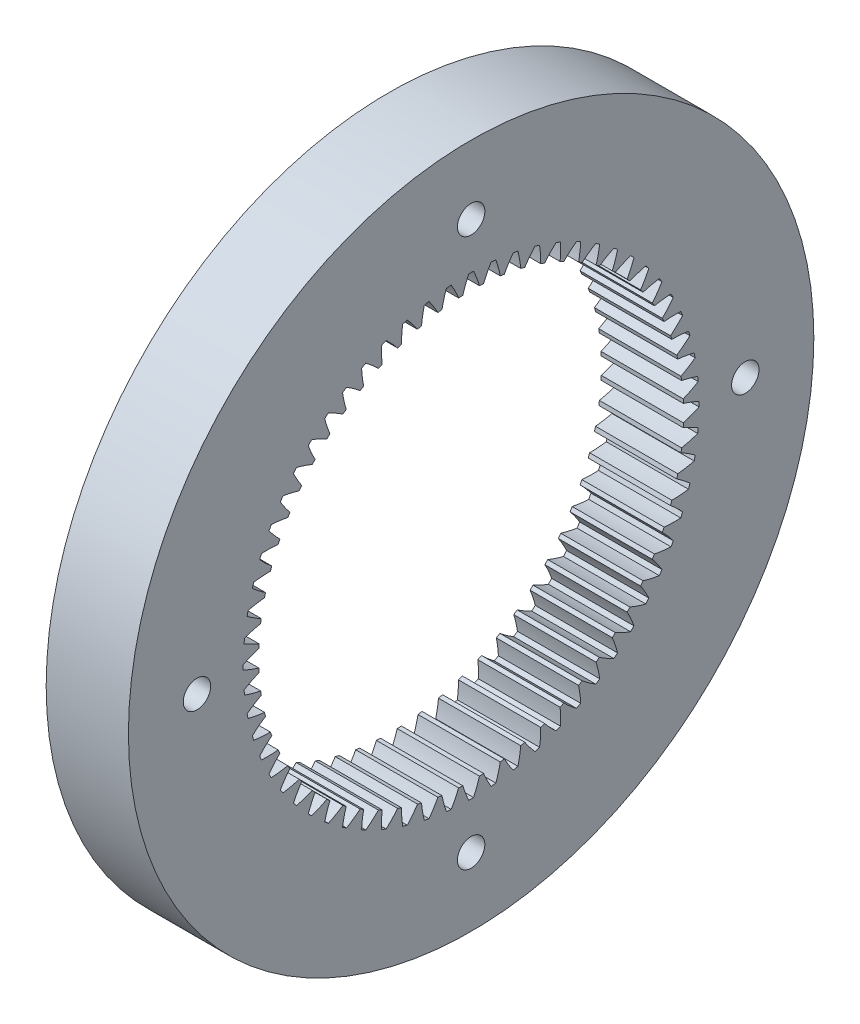
SolidWorks part; units mm, degrees
ref_plane "Plane1" through (0, 0, 0) normal (0, 0, 1) x (1, 0, 0)
ref_plane "Plane2" through (0, 0, 0) normal (0, 1, 0) x (1, 0, 0)
ref_plane "Plane3" through (0, 0, 0) normal (1, 0, 0) x (0, 0, -1)
sketch "HoldingSke" plane through (0, 0, 0) normal (0, 1, 0) x (1, 0, 0)
  line L0 (0, 0) -> (0.4384, -0.8988)
  line L1 (-15, 0) -> (100, 0) construction
  line L2 (0, 0) -> (-2.1039, 2.3779)
  line L3 (0, 0) -> (-11.863, 4.5341)
  line L4 (0, 0) -> (3.7858, 7.762)
  line L5 (0, 0) -> (-23.7986, -8.8762)
  line L6 (0, 0) -> (-10.5278, -7.1032)
  line L7 (-2.1039, 2.3779) -> (3.3635, 27.1825)
  line L8 (-76.2, 3.3779) -> (-54.61, 3.3779)
  line L9 (-71.009, 38.7566) -> (-53.1078, 45.2721)
  line L10 (-76.2, 71.12) -> (104.1128, 71.12)
  line L11 (0, 0) -> (-12, 0)
  line L12 (-76.2, 101.6) -> (-76.162, 101.6)
  line L13 (24.9733, 27.94) -> (52.9518, 28.4284)
  line L14 (24.9733, 27.94) -> (24.9743, 27.94)
  line L15 (24.9733, 27.94) -> (100.4006, 29.5858)
  circle A0 centre (0, 0) radius 50
  circle A1 centre (0, 0) radius 12.7
  circle A2 centre (0, 0) radius 12.7
  dimension "MHD" = 25.4
  dimension "Hub_dia" = 25.4
  dimension "Diameter" = 100
  dimension "Num_teeth" = 64
  dimension "Pitch" = 1
  dimension "Overall_len" = 25.4
  dimension "Show_teeth" = 64
  dimension "Thickness" = 12.7
  dimension "OAL" = 25.4001
  dimension "T_dim" = 21.59
  dimension "Ap" = 20
  dimension "H" = 19.05
  dimension "Pitch_radius" = 180.3128
  dimension "Width" = 12
  dimension "Backlash" = 0.038
  dimension "Addendum_fac" = 1
  dimension "Dedendum_fac" = 1.25
  dimension "Clearance_fac" = 0.25
  dimension "Dedendum_add" = 0.001
  dimension "Module" = 1
sketch "BasProSke" plane through (0, 0, 0) normal (0, 1, 0) x (1, 0, 0)
  line L0 (-10, 0) -> (60, 0) construction
  line L1 (0, 31) -> (0, 50)
  line L2 (0, 31) -> (12, 31)
  line L3 (12, 31) -> (12, 50)
  line L4 (12, 50) -> (0, 50)
  dimension "Diameter" = 100
  dimension "Thickness" = 12
  dimension "Inside_diameter" = 62
revolve "Base-Revolve" add sketch "BasProSke" angle 360 about L0
sketch "TooCutSke" plane through (0, 0, 0) normal (1, 0, 0) x (0, 0, -1)
  line L3 (0.8803, 31.9879) -> (0.8803, 53.6633) construction
  line L4 (0, 0) -> (0, 59.563) construction
  line L5 (0, 0) -> (-3.3527, 68.2452) construction
  line L6 (-14.1131, 26.4025) -> (36.4693, 28.8874) construction
  circle A0 centre (0, 0) radius 32 construction
  circle A1 centre (0, 0) radius 33.251 construction
  circle A2 centre (0, 0) radius 27.0631 construction
  circle A3 centre (0, 0) radius 30.9746 construction
  arc A4 (1.2269, 30.9503) -> (0.348, 33.2492) centre (-14.1131, 26.4025) ccw
  arc A5 (1.2269, 30.9503) -> (-1.2269, 30.9503) centre (0, 0) ccw
  arc A6 (0.348, 33.2492) -> (-0.348, 33.2492) centre (0, 0) ccw
  arc A7 (-0.348, 33.2492) -> (-1.2269, 30.9503) centre (14.1131, 26.4025) ccw
  dimension "Pitch_dia" = 64
  dimension "Base_dia" = 54.1263
  dimension "Root_dia" = 66.502
  dimension "Overcut_dia" = 61.9492
  dimension "Flank_rad" = 16
  dimension "Half_ang" = 2.813
  dimension "Half_CT" = 0.8803
extrude "ToothCut" cut sketch "TooCutSke" along normal through all
fillet "Breaks" [suppressed] radius 0.1
fillet "RootFillets" [suppressed] radius 0.251
pattern_circular "TeethCuts" count 64 every 5.625 about axis through (-10, 0, 0) along (1, 0, 0) of "RootFillets", "Breaks", "ToothCut"
sketch "Sketch1" plane through (12, 0, 0) normal (1, 0, 0) x (0, 0, -1)
  line L0 (0, 0) -> (0, 60.9893) construction
  line L1 (0, 0) -> (100.1632, 0) construction
  line L2 (-40, 0) -> (0, 0) construction
  line L3 (0, 0) -> (40, 0) construction
  line L4 (0, 40) -> (0, 0) construction
  line L5 (0, -40) -> (0, 0) construction
  circle A0 centre (0, 40) radius 2
  circle A1 centre (0, -40) radius 2
  circle A2 centre (-40, 0) radius 2
  circle A3 centre (40, 0) radius 2
  point P4 (0, 0)
  dimension "D1" = 4
  dimension "D2" = 40
extrude "Cut-Extrude1" cut sketch "Sketch1" against normal through all
equation "' \"Module@HoldingSke\" = 6.35"
equation "' \"Num_teeth@HoldingSke\" = 24"
equation "' \"Ap@HoldingSke\" =  14.5"
equation "' \"Ap@HoldingSke\" = 14.5"
equation "' \"Width@HoldingSke\" = 12"
equation "' \"Diameter@HoldingSke\" = 8 * 25.4"
equation "' \"Show_teeth@HoldingSke\" = 100"
equation "' \"Backlash@HoldingSke\" = 0.009 * 25.4"
equation "' \"Addendum_fac@HoldingSke\" = 1.0"
equation "' \"Dedendum_fac@HoldingSke\" = 1.25"
equation "' \"Dedendum_add@HoldingSke\" = 0.00005 * 25.4"
equation "' \"Clearance_fac@HoldingSke\" = 0.25"
equation "\"Pitch@HoldingSke\" = 1 / \"Module@HoldingSke\" "
equation "\"Overcut_dia@TooCutSke\" = (\"Num_teeth@HoldingSke\" - 2 * \"Addendum_fac@HoldingSke\") / \"Pitch@HoldingSke\" - 0.002 * 25.4"
equation "\"Pitch_dia@TooCutSke\" = \"Num_teeth@HoldingSke\" / \"Pitch@HoldingSke\""
equation "\"Base_dia@TooCutSke\" = \"Num_teeth@HoldingSke\" / \"Pitch@HoldingSke\" * cos((\"Ap@HoldingSke\"  * 3.14159265 / 180)) * 0.90"
equation "\"Root_dia@TooCutSke\" = \"Num_teeth@HoldingSke\"  / \"Pitch@HoldingSke\" + 2 *  \"Dedendum_fac@HoldingSke\"/ \"Pitch@HoldingSke\" + \"Dedendum_add@HoldingSke\" * 2"
equation "\"Half_ang@TooCutSke\" = 180 / \"Num_teeth@HoldingSke\""
equation "\"Half_CT@TooCutSke\" = \"Num_teeth@HoldingSke\" / \"Pitch@HoldingSke\" * sin((3.14159265 / 2 / \"Num_teeth@HoldingSke\")) / 2 + 10 * \"Backlash@HoldingSke\" / 4"
equation "\"Flank_rad@TooCutSke\" = \"Num_teeth@HoldingSke\" / \"Pitch@HoldingSke\" / 4"
equation "\"Radius@RootFillets\"= \"Clearance_fac@HoldingSke\" / \"Pitch@HoldingSke\" + \"Dedendum_add@HoldingSke\""
equation "\"Break_rad@Breaks\" = 0.02 / \"Pitch@HoldingSke\" * 5"
equation "\"Num_teeth@TeethCuts\" = int( \"Show_teeth@HoldingSke\" ) + 1"
equation "\"Num_teeth@TeethCuts\" = ((sgn( \"Num_teeth@TeethCuts\" - \"Num_teeth@HoldingSke\" )-1)*( \"Num_teeth@TeethCuts\" - \"Num_teeth@HoldingSke\" ))/-2+ \"Num_teeth@HoldingSke\""
equation "\"Num_teeth@TeethCuts\" = ((sgn( \"Num_teeth@TeethCuts\" - 2.0)+1)*( \"Num_teeth@TeethCuts\" - 2.0))/2 +2.0"
equation "\"Angle@TeethCuts\" = 360.0 / \"Num_teeth@HoldingSke\""
equation "\"Diameter@BasProSke\" = \"Num_teeth@HoldingSke\"  / \"Pitch@HoldingSke\" + 2 *  \"Dedendum_fac@HoldingSke\"/ \"Pitch@HoldingSke\" + \"Dedendum_add@HoldingSke\" * 2 + 0.002 * 25.4"
equation "\"Diameter@BasProSke\" = ((sgn( \"Diameter@BasProSke\"  - \"Diameter@HoldingSke\" )+1)*( \"Diameter@BasProSke\"  - \"Diameter@HoldingSke\" ))/2 + \"Diameter@HoldingSke\""
equation "\"Inside_diameter@BasProSke\" =  (\"Num_teeth@HoldingSke\" - 2 * \"Addendum_fac@HoldingSke\") / \"Pitch@HoldingSke\" "
equation "\"Thickness@BasProSke\"  = \"Width@HoldingSke\""
